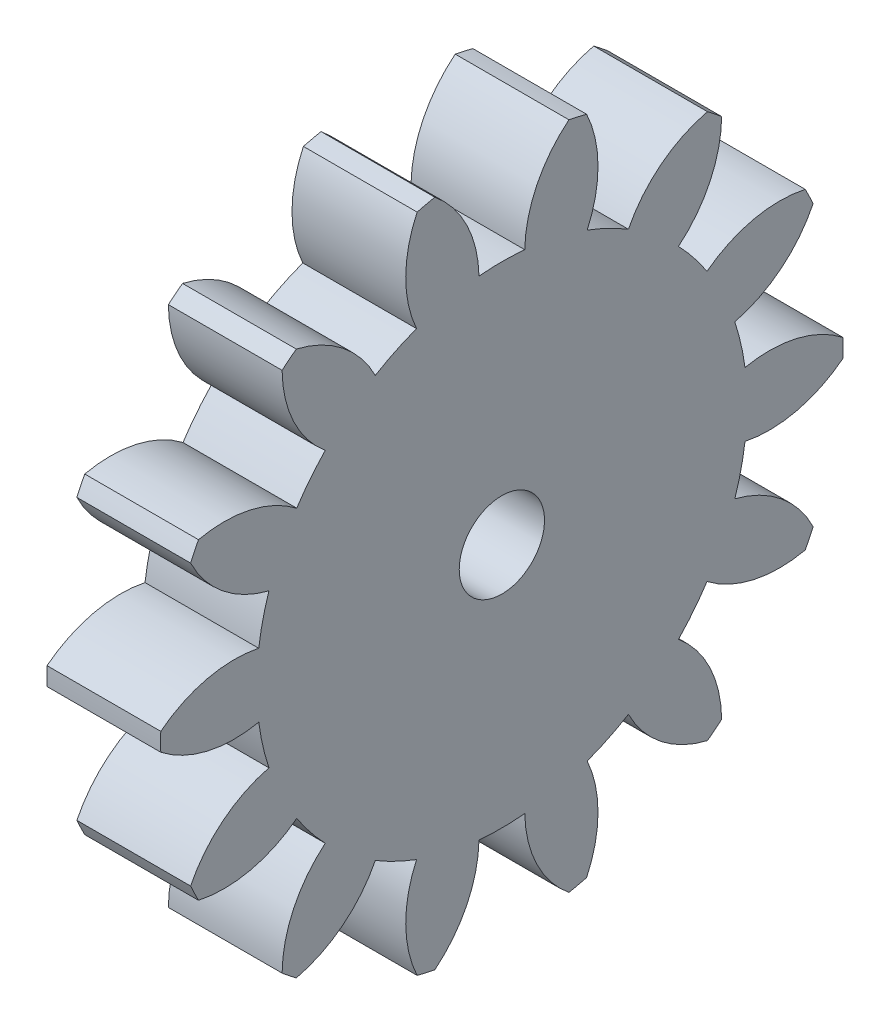
SolidWorks part; units mm, degrees
ref_plane "Plane1" through (0, 0, 0) normal (0, 0, 1) x (1, 0, 0)
ref_plane "Plane2" through (0, 0, 0) normal (0, 1, 0) x (1, 0, 0)
ref_plane "Plane3" through (0, 0, 0) normal (1, 0, 0) x (0, 0, -1)
sketch "HoldingSke" plane through (0, 0, 0) normal (0, 1, 0) x (1, 0, 0)
  line L0 (0, 0) -> (0.6469, -0.1613)
  line L1 (-15, 0) -> (100, 0) construction
  line L2 (0, 0) -> (-2.1039, 2.3779)
  line L3 (0, 0) -> (-11.863, 4.5341)
  line L4 (0, 0) -> (8.3795, 2.0892)
  line L5 (0, 0) -> (-46.8476, -17.4728)
  line L6 (0, 0) -> (-3.3159, -2.2372)
  line L7 (-2.1039, 2.3779) -> (8.6586, 51.2059)
  line L8 (-76.2, 54.61) -> (-75.7, 54.61)
  line L9 (-71.009, 38.7566) -> (-53.1078, 45.2721)
  line L10 (-76.2, 71.12) -> (104.1128, 71.12)
  line L11 (0, 0) -> (-4, 0)
  line L12 (-76.2, 101.6) -> (-76.147, 101.6)
  line L13 (24.9733, 27.94) -> (52.9518, 28.4284)
  line L14 (24.9733, 27.94) -> (24.9743, 27.94)
  line L15 (24.9733, 27.94) -> (100.4006, 29.5858)
  line L16 (-63.627, -1.5) -> (-12.827, -1.5)
  circle A0 centre (0, 0) radius 1.5
  circle A1 centre (0, 0) radius 8.624
  circle A2 centre (0, 0) radius 37.5
  circle A3 centre (0, 0) radius 1.5
  dimension "MHD" = 17.248
  dimension "Hub_dia" = 75
  dimension "Bore" = 3
  dimension "MBD" = 3
  dimension "Num_teeth" = 14
  dimension "Pitch" = 0.6667
  dimension "Overall_len" = 50
  dimension "Show_teeth" = 14
  dimension "Thickness" = 4
  dimension "OAL" = 50.0001
  dimension "T_dim" = 0.5
  dimension "Ap" = 20
  dimension "H" = 19.05
  dimension "Pitch_radius" = 180.3128
  dimension "Width" = 4
  dimension "Backlash" = 0.053
  dimension "Addendum_fac" = 1
  dimension "Dedendum_fac" = 1.25
  dimension "Clearance_fac" = 0.25
  dimension "Dedendum_add" = 0.001
  dimension "Module" = 1.5
sketch "BasProSke" plane through (0, 0, 0) normal (0, 1, 0) x (1, 0, 0)
  line L0 (-10, 0) -> (60, 0) construction
  line L1 (0, 0) -> (0, 12)
  line L2 (0, 0) -> (4, 0)
  line L3 (4, 0) -> (4, 12)
  line L4 (4, 12) -> (0, 12)
  dimension "Thickness" = 4
  dimension "Diameter" = 24
revolve "Base-Revolve" add sketch "BasProSke" angle 360 about L0
sketch "TooCutSke" plane through (0, 0, 0) normal (1, 0, 0) x (0, 0, -1)
  line L1 (0, 0) -> (0, 107) construction
  line L2 (0, 0) -> (-1.2683, 10.4231) construction
  line L3 (0, 0) -> (-4.648, 20.3643) construction
  line L4 (-1.2683, 10.4231) -> (-2.324, 10.1822) construction
  arc A0 (0.8048, 8.5864) -> (-0.8048, 8.5864) centre (0, 0) ccw
  arc A1 (2.3844, 11.7866) -> (-2.3844, 11.7866) centre (0, 0) ccw
  circle A2 centre (0, 0) radius 10.5 construction
  circle A3 centre (0, 0) radius 9.8668 construction
  arc A4 (-0.8048, 8.5864) -> (-2.3844, 11.7866) centre (-5.004, 8.5037) ccw
  arc A5 (2.3844, 11.7866) -> (0.8048, 8.5864) centre (5.004, 8.5037) ccw
  dimension "Root_dia" = 17.248
  dimension "Overcut_dia" = 24.0508
  dimension "Pitch_dia" = 21
  dimension "Base_dia" = 19.7335
  dimension "Flank_rad" = 4.2
  dimension "Half_ang" = 12.857
  dimension "Half_CT" = 1.0829
extrude "ToothCut" cut sketch "TooCutSke" along normal through all
fillet "Breaks" [suppressed] radius 0.03
fillet "RootFillets" [suppressed] radius 0.376
pattern_circular "TeethCuts" count 14 every 25.714 about axis through (-10, 0, 0) along (1, 0, 0) of "ToothCut", "RootFillets", "Breaks"
sketch "HubNeaOneSke" plane through (0, 0, 0) normal (-1, 0, 0) x (0, 0, 1)
  circle A0 centre (0, 0) radius 8.624
  dimension "Diameter" = 17.248
extrude "HubNearOne" [suppressed] add sketch "HubNeaOneSke" along normal blind 46.0001
sketch "HubNeaBotSke" plane through (0, 0, 0) normal (-1, 0, 0) x (0, 0, 1)
  circle A0 centre (0, 0) radius 8.624
  dimension "Diameter" = 17.248
extrude "HubNearBoth" [suppressed] add sketch "HubNeaBotSke" along normal blind 23
ref_plane "FarPln" through (4, 0, 0) normal (1, 0, 0) x (0, 0, -1)
sketch "HubFarSke" plane through (4, 0, 0) normal (1, 0, 0) x (0, 0, -1)
  circle A0 centre (0, 0) radius 8.624
  dimension "Diameter" = 17.248
extrude "HubFar" [suppressed] add sketch "HubFarSke" along normal blind 23
sketch "BorSke" plane through (0, 0, 0) normal (1, 0, 0) x (0, 0, -1)
  circle A0 centre (0, 0) radius 1.5
  dimension "Diameter" = 3
extrude "Bore" cut sketch "BorSke" along normal mid plane 100.0001
sketch "KeySke" plane through (0, 0, 0) normal (1, 0, 0) x (0, 0, -1)
  line L0 (-0.6, 0) -> (-0.6, 2)
  line L1 (-0.6, 2) -> (0.6, 2)
  line L2 (0.6, 2) -> (0.6, 0)
  line L3 (0, 0) -> (0, 34) construction
  line L4 (-0.6, 0) -> (0.6, 0)
  dimension "Offset" = 2
  dimension "Width" = 1.2
extrude "Keyway" [suppressed] cut sketch "KeySke" along normal mid plane 100.0001
pattern_circular "Keyway2" [suppressed] count 2 every 90 about axis through (-10, 0, 0) along (1, 0, 0)
equation "' \"Module@HoldingSke\" = 6.35"
equation "' \"Num_teeth@HoldingSke\" = 12"
equation "' \"Ap@HoldingSke\" =  20"
equation "' \"Ap@HoldingSke\" = 20"
equation "' \"Width@HoldingSke\" = 0.5 * 25.4"
equation "' \"Hub_dia@HoldingSke\"= 1 * 25.4"
equation "' \"Hub_dia@HoldingSke\" = 1 * 25.4"
equation "' \"Overall_len@HoldingSke\" = 1.0 * 25.4"
equation "' \"Bore@HoldingSke\" = 0.75 * 25.4"
equation "' \"T_dim@HoldingSke\" = 0.1 * 25.4"
equation "' \"Width@KeySke\" = 0.25 * 25.4"
equation "' \"Show_teeth@HoldingSke\" = 13"
equation "' \"Backlash@HoldingSke\" = 0.009 * 25.4"
equation "' \"Addendum_fac@HoldingSke\" = 1.0"
equation "' \"Dedendum_fac@HoldingSke\" = 1.25"
equation "' \"Dedendum_add@HoldingSke\" = 0.00005 * 25.4"
equation "' \"Clearance_fac@HoldingSke\" = 0.25"
equation "\"Pitch@HoldingSke\" = 1 / \"Module@HoldingSke\""
equation "\"Overcut_dia@TooCutSke\" = (\"Num_teeth@HoldingSke\" + 2 * \"Addendum_fac@HoldingSke\") / \"Pitch@HoldingSke\" + 0.002 * 25.4"
equation "\"Pitch_dia@TooCutSke\" = \"Num_teeth@HoldingSke\" / \"Pitch@HoldingSke\""
equation "\"Base_dia@TooCutSke\" = \"Num_teeth@HoldingSke\" / \"Pitch@HoldingSke\" * cos((\"Ap@HoldingSke\"  * 3.14159265 / 180))"
equation "\"Root_dia@TooCutSke\" = (\"Num_teeth@HoldingSke\" + 2) / \"Pitch@HoldingSke\" - 2 * (\"Addendum_fac@HoldingSke\" + \"Dedendum_fac@HoldingSke\") / \"Pitch@HoldingSke\" - \"Dedendum_add@HoldingSke\" * 2"
equation "\"Half_ang@TooCutSke\" = 180 / \"Num_teeth@HoldingSke\""
equation "\"Half_CT@TooCutSke\" = \"Num_teeth@HoldingSke\" / \"Pitch@HoldingSke\" * sin((3.14159265 / 2 / \"Num_teeth@HoldingSke\")) / 2 - 7 * \"Backlash@HoldingSke\" / 4"
equation "\"Flank_rad@TooCutSke\" = \"Num_teeth@HoldingSke\" / \"Pitch@HoldingSke\" / 5"
equation "\"Radius@RootFillets\" = \"Clearance_fac@HoldingSke\" / \"Pitch@HoldingSke\" + \"Dedendum_add@HoldingSke\""
equation "\"Break_rad@Breaks\" = 0.02 / \"Pitch@HoldingSke\""
equation "\"Thickness@HoldingSke\" = \"Width@HoldingSke\""
equation "\"OAL@HoldingSke\" = \"Thickness@HoldingSke\""
equation "\"MHD@HoldingSke\" = (\"Num_teeth@HoldingSke\" + 2) / \"Pitch@HoldingSke\" - 2 * (\"Addendum_fac@HoldingSke\" + \"Dedendum_fac@HoldingSke\")  / \"Pitch@HoldingSke\" - \"Dedendum_add@HoldingSke\" * 2"
equation "\"MBD@HoldingSke\" = (\"Num_teeth@HoldingSke\" + 2) / \"Pitch@HoldingSke\" - 2 * (\"Addendum_fac@HoldingSke\" + \"Dedendum_fac@HoldingSke\")  / \"Pitch@HoldingSke\" - \"Dedendum_add@HoldingSke\" * 2 - 0.002 * 25.4"
equation "\"MHD@HoldingSke\" = ((sgn( \"MHD@HoldingSke\" - \"Hub_dia@HoldingSke\" )-1)*( \"MHD@HoldingSke\" - \"Hub_dia@HoldingSke\" ))/-2+ \"Hub_dia@HoldingSke\""
equation "\"MBD@HoldingSke\" = ((sgn( \"MBD@HoldingSke\" - \"Bore@HoldingSke\" )-1)*( \"MBD@HoldingSke\" - \"Bore@HoldingSke\" ))/-2+ \"Bore@HoldingSke\""
equation "\"OAL@HoldingSke\" = ((sgn( \"OAL@HoldingSke\" - \"Overall_len@HoldingSke\" )+1)*( \"OAL@HoldingSke\" - \"Overall_len@HoldingSke\" ))/2 + \"Overall_len@HoldingSke\" + 0.000002 * 25.4"
equation "\"Num_teeth@TeethCuts\" = int( \"Show_teeth@HoldingSke\" ) + 1"
equation "\"Num_teeth@TeethCuts\" = ((sgn( \"Num_teeth@TeethCuts\" - \"Num_teeth@HoldingSke\" )-1)*( \"Num_teeth@TeethCuts\" - \"Num_teeth@HoldingSke\" ))/-2+ \"Num_teeth@HoldingSke\""
equation "\"Num_teeth@TeethCuts\" = ((sgn( \"Num_teeth@TeethCuts\" - 2.0)+1)*( \"Num_teeth@TeethCuts\" - 2.0))/2 +2.0"
equation "\"Angle@TeethCuts\" = 360.0 / \"Num_teeth@HoldingSke\""
equation "\"Diameter@BasProSke\" = (\"Num_teeth@HoldingSke\" + 2 * \"Addendum_fac@HoldingSke\") / \"Pitch@HoldingSke\""
equation "\"Thickness@BasProSke\"  = \"Thickness@HoldingSke\""
equation "' \"Fillet_rad@BasProSke\" =  \"Thickness@HoldingSke\" * 0.05"
equation "' \"Fillet_rad@BasProSke\" = \"Thickness@HoldingSke\" * 0.05"
equation "\"MHD@HoldingSke\" = ((sgn( \"MHD@HoldingSke\" - \"Root_dia@TooCutSke\" )-1)*( \"MHD@HoldingSke\" - \"Root_dia@TooCutSke\" ))/-2+ \"Root_dia@TooCutSke\""
equation "\"Diameter@HubNeaOneSke\" = \"MHD@HoldingSke\""
equation "\"Length@HubNearOne\" = \"OAL@HoldingSke\" - \"Thickness@BasProSke\""
equation "\"Diameter@HubNeaBotSke\" = \"MHD@HoldingSke\""
equation "\"Length@HubNearBoth\" = ( \"OAL@HoldingSke\" - \"Thickness@BasProSke\" ) / 2.0"
equation "\"Thickness@FarPln\" = \"Thickness@BasProSke\""
equation "\"Diameter@HubFarSke\" = \"MHD@HoldingSke\""
equation "\"Length@HubFar\" = ( \"OAL@HoldingSke\" - \"Thickness@BasProSke\" ) / 2.0"
equation "\"Diameter@BorSke\" = \"MBD@HoldingSke\""
equation "\"D1@Bore\" = \"OAL@HoldingSke\" * 2.0"
equation "\"D1@Keyway\" = \"OAL@HoldingSke\" * 2.0"
equation "\"Offset@KeySke\" = \"T_dim@HoldingSke\" + \"MBD@HoldingSke\" / 2.0"
